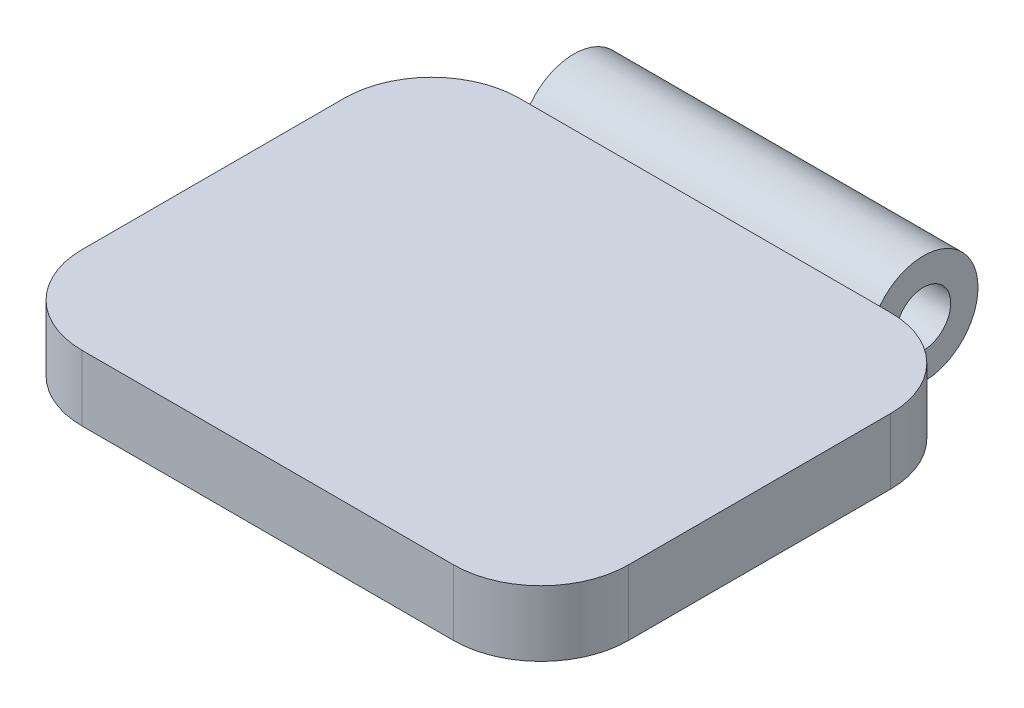
SolidWorks part; units mm, degrees
ref_plane "Front Plane" through (0, 0, 0) normal (0, 0, 1) x (1, 0, 0)
ref_plane "Top Plane" through (0, 0, 0) normal (0, 1, 0) x (1, 0, 0)
ref_plane "Right Plane" through (0, 0, 0) normal (1, 0, 0) x (0, 0, -1)
sketch "Sketch2" plane through (0, 0, 0) normal (0, 1, 0) x (1, 0, 0)
  line L1 (-12.5, -10) -> (12.5, -10)
  line L2 (-12.5, -10) -> (-12.5, 10)
  line L3 (-12.5, 10) -> (12.5, 10)
  line L4 (12.5, -10) -> (12.5, 10)
  line L5 (-12.5, -10) -> (12.5, 10) construction
  line L6 (-12.5, 10) -> (12.5, -10) construction
  point P0 (0, 0)
  dimension "D1" = 25
  dimension "D2" = 20
extrude "Boss-Extrude1" add sketch "Sketch2" along normal blind 3
fillet "Fillet1" radius 4 4 edges at (-12.5, 1.5, -10) (-12.5, 1.5, 10) (12.5, 1.5, -10) (12.5, 1.5, 10)
sketch "Sketch4" plane through (0, 0, 0) normal (1, 0, 0) x (0, 0, -1)
  line L0 (10, 3) -> (10, 0) construction
  line L2 (6, 1.5) -> (17.7036, 1.5) construction
  line L3 (6, 0) -> (6, 3) construction
  circle A0 centre (12, 1.5) radius 2.5
  dimension "D1" = 5
  dimension "D2" = 2
  dimension "D3" = 0
extrude "Boss-Extrude2" add sketch "Sketch4" along normal mid plane 16
sketch "Sketch5" plane through (8, 0, 0) normal (1, 0, 0) x (0, 0, -1)
  circle A0 centre (12, 1.5) radius 1.25
  dimension "D1" = 2.5
extrude "Cut-Extrude1" cut sketch "Sketch5" against normal blind 16
